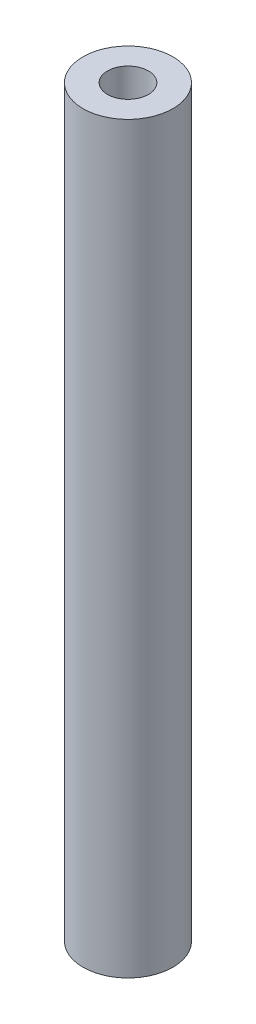
SolidWorks part; units mm, degrees
material "Plain Carbon Steel"
ref_plane "Front Plane" through (0, 0, 0) normal (0, 0, 1) x (1, 0, 0)
ref_plane "Top Plane" through (0, 0, 0) normal (0, 1, 0) x (1, 0, 0)
ref_plane "Right Plane" through (0, 0, 0) normal (1, 0, 0) x (0, 0, -1)
sketch "Sketch1" plane through (0, 0, 0) normal (0, 1, 0) x (1, 0, 0)
  circle A0 centre (0, 0) radius 2.5
  circle A1 centre (0, 0) radius 5.5
  dimension "D1" = 3
  dimension "D2" = 5
extrude "Boss-Extrude1" add sketch "Sketch1" along normal blind 91
